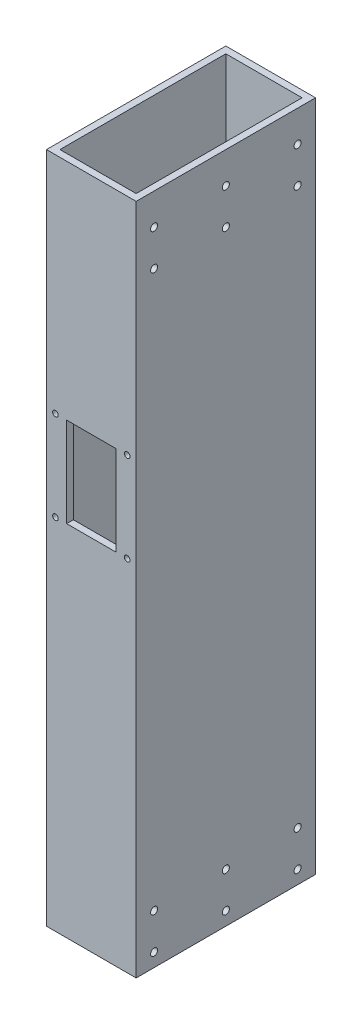
SolidWorks part; units mm, degrees
material "6061-T6 (SS)"
ref_plane "Front Plane" through (0, 0, 0) normal (0, 0, 1) x (1, 0, 0)
ref_plane "Top Plane" through (0, 0, 0) normal (0, 1, 0) x (1, 0, 0)
ref_plane "Right Plane" through (0, 0, 0) normal (1, 0, 0) x (0, 0, -1)
sketch "Sketch1" plane through (0, 0, 0) normal (0, 1, 0) x (1, 0, 0)
  line L0 (3, 3) -> (3, 77)
  line L1 (0, 0) -> (40, 0)
  line L2 (0, 0) -> (0, 80)
  line L3 (0, 80) -> (40, 80)
  line L4 (40, 0) -> (40, 80)
  line L5 (3, 77) -> (37, 77)
  line L6 (37, 3) -> (37, 77)
  line L7 (3, 3) -> (37, 3)
  dimension "D1" = 80
  dimension "D2" = 40
  dimension "D3" = 3
extrude "Boss-Extrude1" add sketch "Sketch1" along normal blind 300
sketch "Sketch2" plane through (0, 0, 0) normal (0, 0, 1) x (1, 0, 0)
  line L0 (20, 300) -> (20, 200) construction
  line L1 (9, 200) -> (31, 200)
  line L2 (9, 200) -> (9, 160)
  line L3 (9, 160) -> (31, 160)
  line L4 (31, 200) -> (31, 160)
  line L5 (0, 300) -> (40, 300) construction
  dimension "D1" = 22
  dimension "D2" = 100
  dimension "D3" = 40
extrude "Cut-Extrude1" cut sketch "Sketch2" against normal up to next
sketch "Sketch3" plane through (0, 0, 0) normal (0, 0, 1) x (1, 0, 0)
  line L0 (9, 200) -> (9, 160) construction
  line L2 (31, 160) -> (31, 200) construction
  line L3 (4, 200) -> (9, 200) construction
  point P0 (4, 200)
  point P11 (36, 200)
  point P12 (36, 160)
  point P13 (4, 160)
  dimension "D1" = 5
  dimension "D5" = 5
  dimension "D6" = 40
  dimension "D3" = 2
  dimension "D4" = 2
hole_wizard "Tap Drill for M3 Tap1" positions "Sketch3" profile "Sketch5" hole size "M3" standard "DIN"
sketch "Sketch5" plane through (4, 200, 0) normal (1, 0, 0) x (0, -1, 0)
  line L0 (0, 0) -> (0, 3)
  line L1 (0, 3) -> (1.25, 3)
  line L2 (1.25, 3) -> (1.25, 0)
  line L5 (1.25, 0) -> (0, 0)
  line L11 (0, -6.35) -> (0, 107.95) construction
  dimension "Thru Hole Dia." = 2.5
  dimension "Thru Hole Depth" = 3
sketch "Sketch8" plane through (0, 0, 0) normal (-1, 0, 0) x (0, 0, 1)
  point P0 (-8, 6)
  point P8 (-40, 6)
  point P9 (-72, 6)
  point P10 (-40, 22)
  point P11 (-72, 22)
  point P12 (-8, 22)
  dimension "D1" = 3
  dimension "D2" = 2
hole_wizard "Tap Drill for M3 Helicoil1" positions "Sketch8" profile "Sketch7" hole size "M3x0.5" standard "DIN" end condition through all
sketch "Sketch7" plane through (0, 6, -8) normal (0, 1, 0) x (0, 0, 1)
  line L0 (0, 0) -> (0, 40)
  line L1 (0, 40) -> (1.575, 40)
  line L2 (1.575, 40) -> (1.575, 0)
  line L5 (1.575, 0) -> (0, 0)
  line L11 (0, -6.35) -> (0, 107.95) construction
  dimension "Thru Hole Dia." = 3.15
  dimension "Thru Hole Depth" = 40
sketch "Sketch11" plane through (40, 0, 0) normal (1, 0, 0) x (0, 0, -1)
  point P0 (72, 286)
  point P3 (72, 270)
  point P6 (40, 286)
  point P9 (40, 270)
  point P12 (8, 286)
  point P15 (8, 270)
hole_wizard "Tap Drill for M3 Helicoil2" positions "Sketch11" profile "Sketch10" hole size "M3x0.5" standard "DIN"
sketch "Sketch10" plane through (40, 286, -72) normal (0, 1, 0) x (0, 0, -1)
  line L0 (0, 0) -> (0, 3)
  line L1 (0, 3) -> (1.575, 3)
  line L2 (1.575, 3) -> (1.575, 0)
  line L5 (1.575, 0) -> (0, 0)
  line L11 (0, -6.35) -> (0, 107.95) construction
  dimension "Thru Hole Dia." = 3.15
  dimension "Thru Hole Depth" = 3
